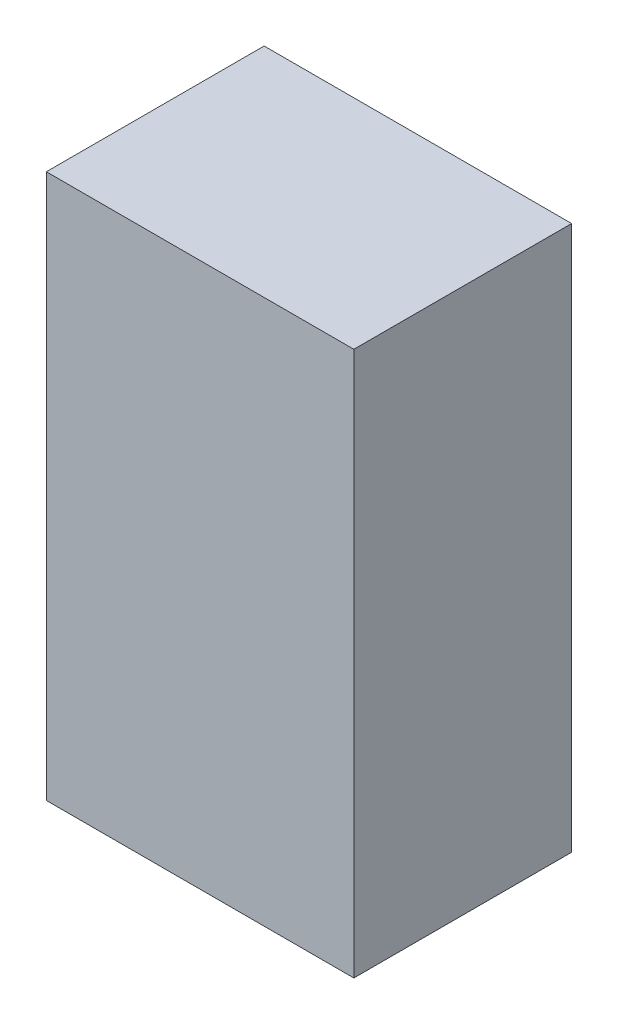
SolidWorks part; units mm, degrees
ref_plane "前视基准面" through (0, 0, 0) normal (0, 0, 1) x (1, 0, 0)
ref_plane "上视基准面" through (0, 0, 0) normal (0, 1, 0) x (1, 0, 0)
ref_plane "右视基准面" through (0, 0, 0) normal (1, 0, 0) x (0, 0, -1)
sketch "草图1" plane through (0, 0, 0) normal (0, 0, 1) x (1, 0, 0)
  line L1 (0, 0) -> (48, 0)
  line L2 (0, 0) -> (0, -85)
  line L3 (0, -85) -> (48, -85)
  line L4 (48, 0) -> (48, -85)
  dimension "D1" = 48
  dimension "D2" = 85
extrude "凸台-拉伸1" add sketch "草图1" along normal blind 34
